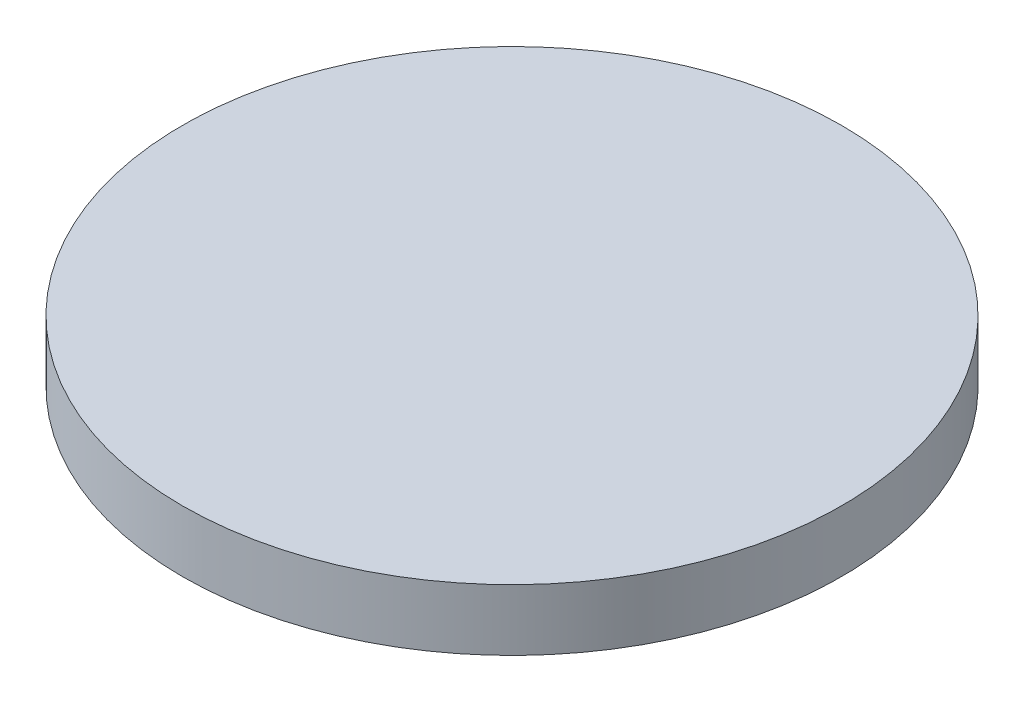
SolidWorks part; units mm, degrees
ref_plane "Front Plane" through (0, 0, 0) normal (0, 0, 1) x (1, 0, 0)
ref_plane "Top Plane" through (0, 0, 0) normal (0, 1, 0) x (1, 0, 0)
ref_plane "Right Plane" through (0, 0, 0) normal (1, 0, 0) x (0, 0, -1)
sketch "Sketch1" plane through (0, 0, 0) normal (0, 1, 0) x (1, 0, 0)
  circle A0 centre (0, 0) radius 21.5
  dimension "D1" = 43
extrude "Boss-Extrude1" add sketch "Sketch1" along normal blind 4
